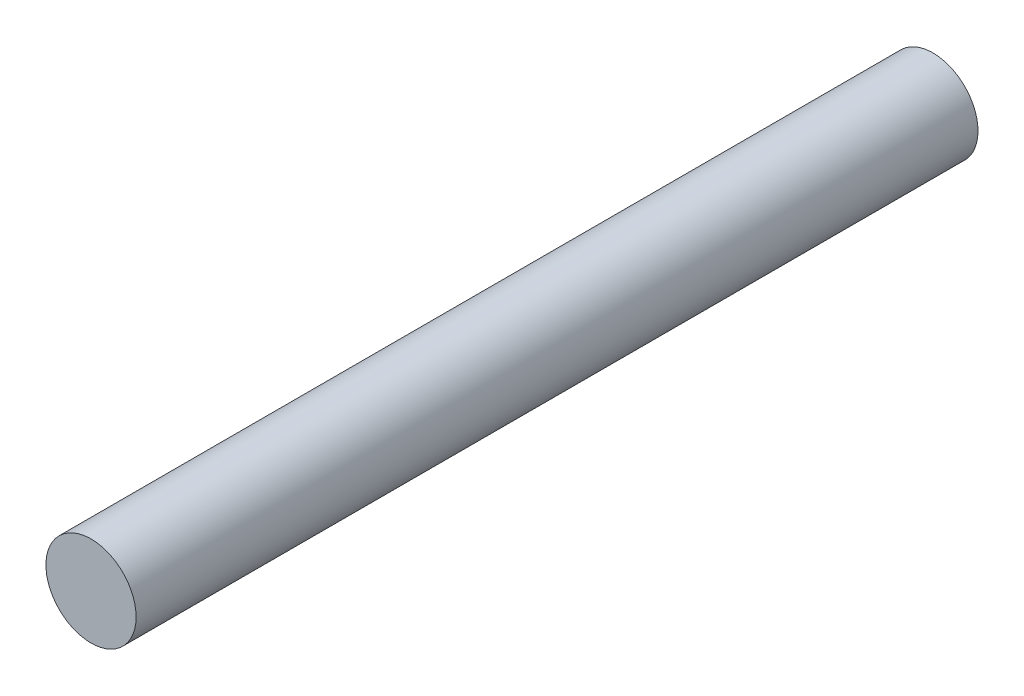
SolidWorks part; units mm, degrees
ref_plane "Alzado" through (0, 0, 0) normal (0, 0, 1) x (1, 0, 0)
ref_plane "Planta" through (0, 0, 0) normal (0, 1, 0) x (1, 0, 0)
ref_plane "Vista lateral" through (0, 0, 0) normal (1, 0, 0) x (0, 0, -1)
sketch "Croquis1" plane through (0, 0, 0) normal (0, 0, 1) x (1, 0, 0)
  circle A0 centre (0, 0) radius 9.525
  dimension "D1" = 19.05
extrude "Saliente-Extruir1" add sketch "Croquis1" along normal blind 177.8
